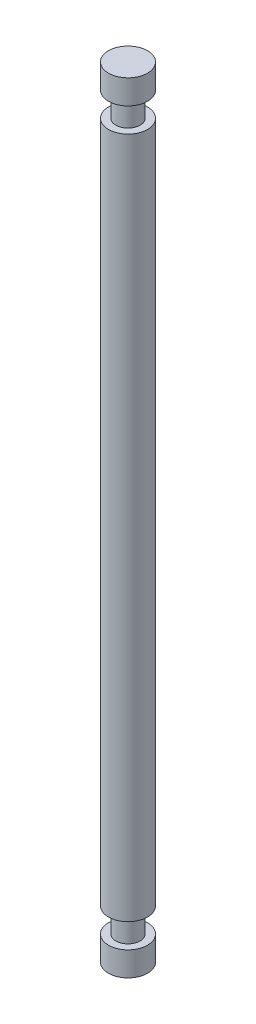
SolidWorks part; units mm, degrees
material "Plain Carbon Steel"
ref_plane "Front Plane" through (0, 0, 0) normal (0, 0, 1) x (1, 0, 0)
ref_plane "Top Plane" through (0, 0, 0) normal (0, 1, 0) x (1, 0, 0)
ref_plane "Right Plane" through (0, 0, 0) normal (1, 0, 0) x (0, 0, -1)
sketch "Sketch1" plane through (0, 0, 0) normal (0, 1, 0) x (1, 0, 0)
  circle A0 centre (0, 0) radius 0.8
  dimension "D1" = 1.6
extrude "Boss-Extrude1" add sketch "Sketch1" along normal blind 30
sketch "Sketch3" plane through (0, 0, 0) normal (0, -1, 0) x (1, 0, 0)
  circle A0 centre (0, 0) radius 0.5
  dimension "D1" = 1
extrude "Boss-Extrude2" add sketch "Sketch3" along normal blind 1
ref_plane "Plane1" through (0, 29, 0) normal (0, 1, 0) x (1, 0, 0)
sketch "Sketch4" plane through (0, 29, 0) normal (0, 1, 0) x (1, 0, 0)
  circle A1 centre (0, 0) radius 0.5
  circle A4 centre (0, 0) radius 0.8
  circle A5 centre (0, 0) radius 0.8
  dimension "D1" = 1
  dimension "D2" = 0
extrude "Cut-Extrude1" cut sketch "Sketch4" against normal blind 1
sketch "Sketch5" plane through (0, -1, 0) normal (0, -1, 0) x (1, 0, 0)
  circle A0 centre (0, 0) radius 0.8
  dimension "D1" = 1.6
extrude "Boss-Extrude3" add sketch "Sketch5" along normal blind 1
